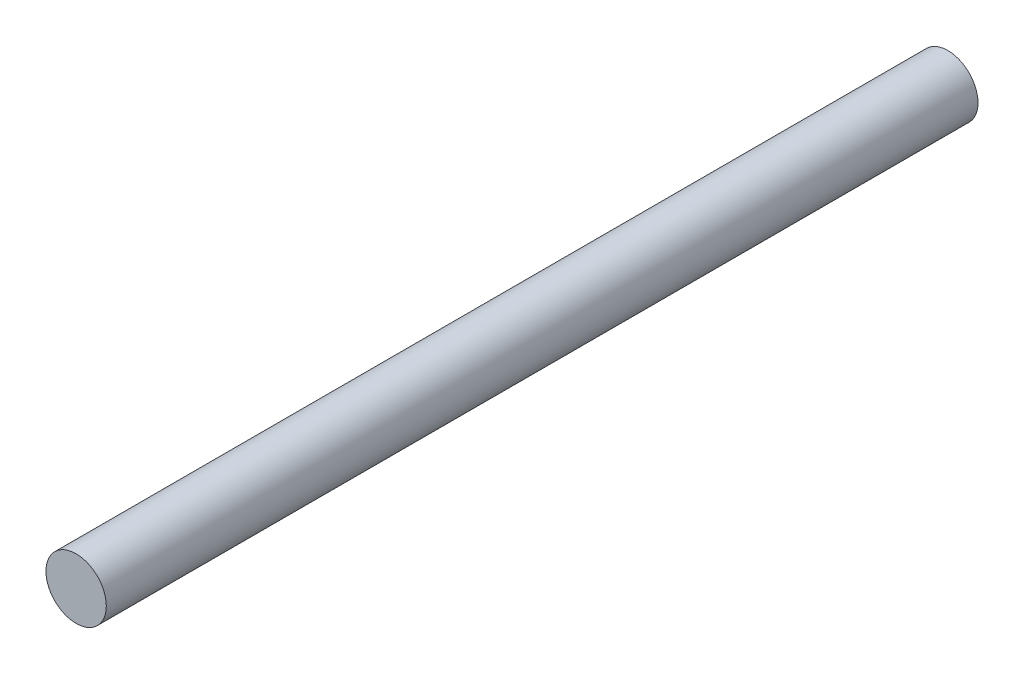
SolidWorks part; units mm, degrees
ref_plane "Front Plane" through (0, 0, 0) normal (0, 0, 1) x (1, 0, 0)
ref_plane "Top Plane" through (0, 0, 0) normal (0, 1, 0) x (1, 0, 0)
ref_plane "Right Plane" through (0, 0, 0) normal (1, 0, 0) x (0, 0, -1)
sketch "Sketch1" plane through (0, 0, 0) normal (0, 0, 1) x (1, 0, 0)
  circle A0 centre (0, 0) radius 2.25
  dimension "D1" = 4.5
extrude "Boss-Extrude1" add sketch "Sketch1" along normal blind 65
